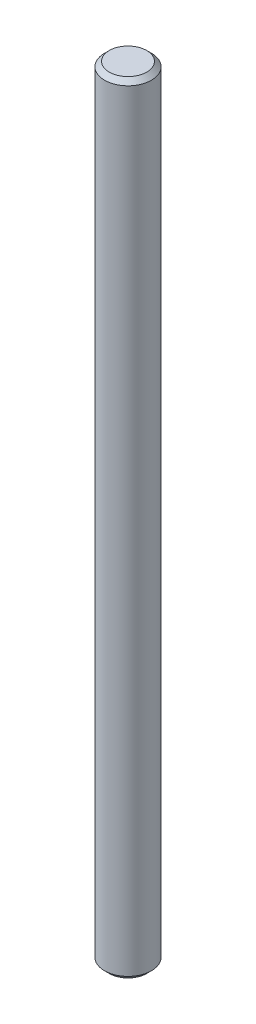
SolidWorks part; units mm, degrees
ref_plane "Plan de face" through (0, 0, 0) normal (0, 0, 1) x (1, 0, 0)
ref_plane "Plan de dessus" through (0, 0, 0) normal (0, 1, 0) x (1, 0, 0)
ref_plane "Plan de droite" through (0, 0, 0) normal (1, 0, 0) x (0, 0, -1)
sketch "Esquisse1" plane through (0, 0, 0) normal (0, 1, 0) x (1, 0, 0)
  circle A0 centre (0, 0) radius 1.5
extrude "Boss.-Extru.1" add sketch "Esquisse1" along normal blind 50
chamfer "Chanfrein1" distance 0.3 angle 45 2 edges at (0, 0, 1.5) (0, 50, 1.5)
